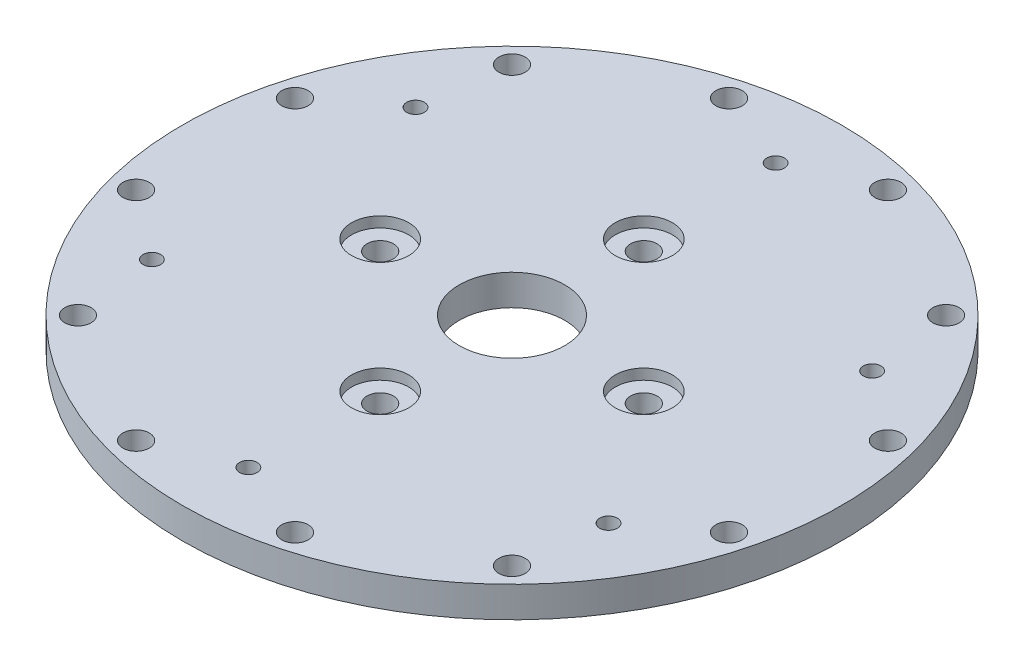
SolidWorks part; units mm, degrees
ref_plane "Front Plane" through (0, 0, 0) normal (0, 0, 1) x (1, 0, 0)
ref_plane "Top Plane" through (0, 0, 0) normal (0, 1, 0) x (1, 0, 0)
ref_plane "Right Plane" through (0, 0, 0) normal (1, 0, 0) x (0, 0, -1)
sketch "Sketch1" plane through (0, 0, 0) normal (0, 1, 0) x (1, 0, 0)
  line L0 (-49.4318, 0) -> (0, 0) construction
  line L1 (0, 0) -> (-47.2333, -12.6561) construction
  circle A0 centre (0, 0) radius 37.5
  circle A1 centre (0, 0) radius 30 construction
  circle A2 centre (0, 0) radius 6
  circle A3 centre (0, 0) radius 15 construction
  circle A4 centre (0, 15) radius 1.5
  circle A5 centre (15, 0) radius 1.5
  circle A6 centre (0, -15) radius 1.5
  circle A7 centre (-15, 0) radius 1.5
  circle A11 centre (0, 0) radius 35 construction
  circle A12 centre (-33.737, -9.0398) radius 1.5
  circle A13 centre (-33.737, 9.0398) radius 1.5
  circle A14 centre (-24.6972, 24.6972) radius 1.5
  circle A15 centre (-9.0398, 33.737) radius 1.5
  circle A16 centre (9.0398, 33.737) radius 1.5
  circle A17 centre (24.6972, 24.6972) radius 1.5
  circle A18 centre (33.737, 9.0398) radius 1.5
  circle A19 centre (33.737, -9.0398) radius 1.5
  circle A20 centre (24.6972, -24.6972) radius 1.5
  circle A21 centre (9.0398, -33.737) radius 1.5
  circle A22 centre (-9.0398, -33.737) radius 1.5
  circle A23 centre (-24.6972, -24.6972) radius 1.5
  circle A24 centre (0, 30) radius 1
  circle A25 centre (25.9808, 15) radius 1
  circle A26 centre (25.9808, -15) radius 1
  circle A27 centre (0, -30) radius 1
  circle A28 centre (-25.9808, -15) radius 1
  circle A29 centre (-25.9808, 15) radius 1
  point P17 (0, 0)
  point P44 (0, 0)
  point P57 (0, 0)
  dimension "D1" = 75
  dimension "D2" = 60
  dimension "D3" = 12
  dimension "D4" = 3
  dimension "D6" = 30
  dimension "D7" = 70
  dimension "D9" = 3
  dimension "D11" = 2
  dimension "D8" = 15
  dimension "D5" = 4
  dimension "D10" = 12
  dimension "D12" = 6
extrude "Boss-Extrude1" add sketch "Sketch1" along normal blind 3.5
sketch "Sketch2" plane through (0, 3.5, 0) normal (0, 1, 0) x (1, 0, 0)
  circle A0 centre (0, 0) radius 15 construction
  circle A1 centre (0, 15) radius 3.25
  circle A2 centre (15, 0) radius 3.25
  circle A3 centre (0, -15) radius 3.25
  circle A4 centre (-15, 0) radius 3.25
  point P15 (0, 0)
  dimension "D1" = 6.5
  dimension "D2" = 4
extrude "Cut-Extrude1" cut sketch "Sketch2" against normal blind 1.2
